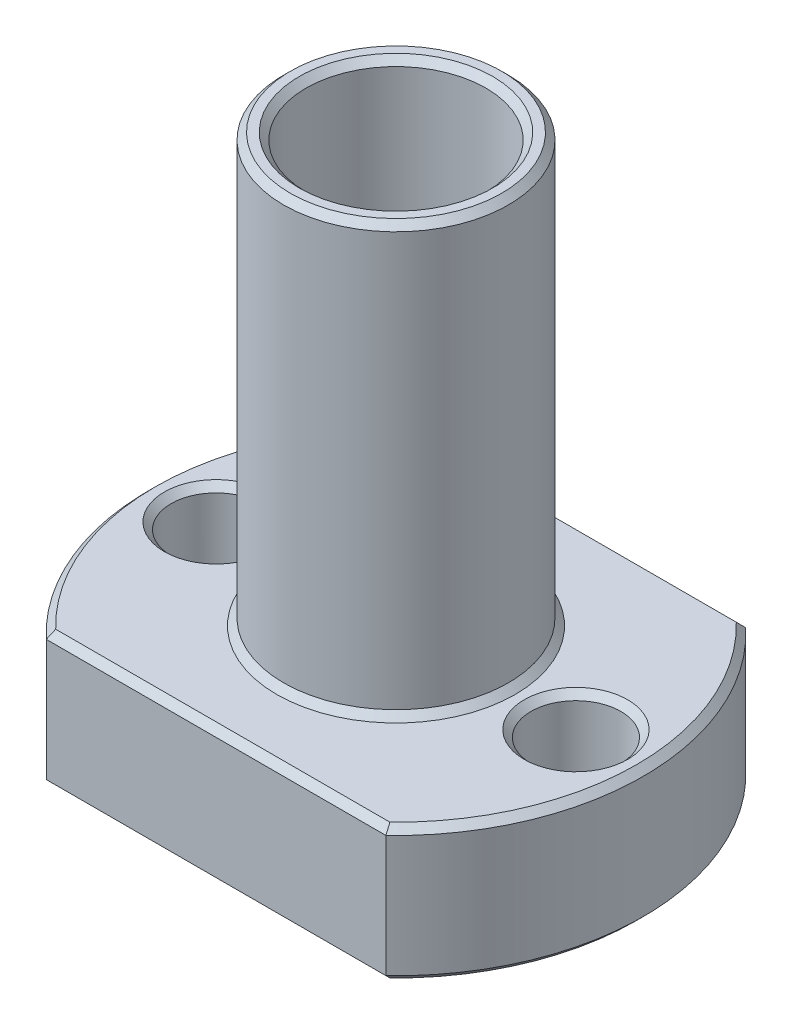
SolidWorks part; units mm, degrees
ref_plane "Alzado" through (0, 0, 0) normal (0, 0, 1) x (1, 0, 0)
ref_plane "Planta" through (0, 0, 0) normal (0, 1, 0) x (1, 0, 0)
ref_plane "Vista lateral" through (0, 0, 0) normal (1, 0, 0) x (0, 0, -1)
sketch "Croquis1" plane through (0, 0, 0) normal (0, 1, 0) x (1, 0, 0)
  line L0 (7.5498, 8) -> (-7.5498, 8)
  line L1 (0, 8) -> (0, -8) construction
  line L2 (7.5498, -8) -> (-7.5498, -8)
  arc A0 (7.5498, -8) -> (7.5498, 8) centre (0, 0) ccw
  circle A1 centre (0, 0) radius 4
  arc A2 (-7.5498, 8) -> (-7.5498, -8) centre (0, 0) ccw
  circle A3 centre (-8, 0) radius 2
  circle A4 centre (8, 0) radius 2
  dimension "D1" = 22
  dimension "D2" = 8
  dimension "D3" = 4
  dimension "D5" = 4
  dimension "D4" = 16
  dimension "D6" = 16
  dimension "D7" = 8
extrude "Saliente-Extruir1" add sketch "Croquis1" along normal blind 6
sketch "Croquis2" plane through (0, 6, 0) normal (0, 1, 0) x (1, 0, 0)
  circle A0 centre (0, 0) radius 5
  circle A1 centre (0, 0) radius 4 construction
  circle A2 centre (0, 0) radius 4
  dimension "D1" = 10
extrude "Saliente-Extruir2" add sketch "Croquis2" along normal blind 19
chamfer "Chaflán1" distance 0.3 angle 45 16 edges at (8, 0, 2) (0, 0, 4) (0, 0, -8) (-11, 0, 0) (0, 0, 8) (11, 0, 0) (-8, 0, 2) (0, 25, 4) (0, 25, 5) (0, 6, 5) (-8, 6, 2) (0, 6, 8) (-11, 6, 0) (0, 6, -8) (11, 6, 0) (8, 6, 2)
